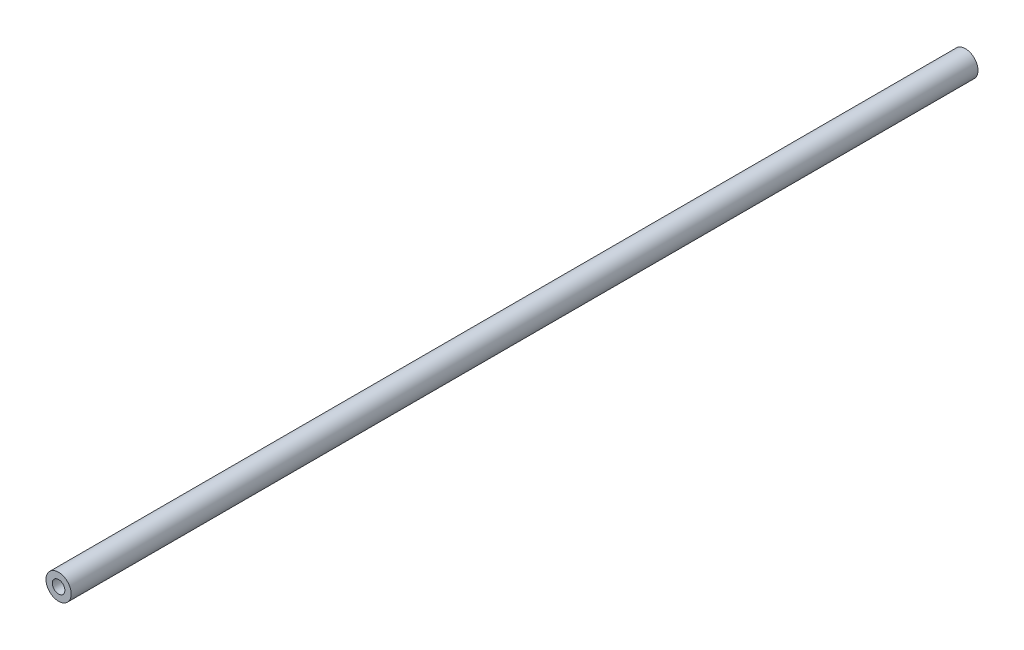
SolidWorks part; units mm, degrees
ref_plane "Front Plane" through (0, 0, 0) normal (0, 0, 1) x (1, 0, 0)
ref_plane "Top Plane" through (0, 0, 0) normal (0, 1, 0) x (1, 0, 0)
ref_plane "Right Plane" through (0, 0, 0) normal (1, 0, 0) x (0, 0, -1)
sketch "Sketch1" plane through (0, 0, 0) normal (0, 0, 1) x (1, 0, 0)
  circle A0 centre (0, 0) radius 1.5875
  circle A1 centre (0, 0) radius 0.7937
  dimension "D1" = 3.175
  dimension "D2" = 1.5875
extrude "Boss-Extrude1" add sketch "Sketch1" along normal blind 114.3
